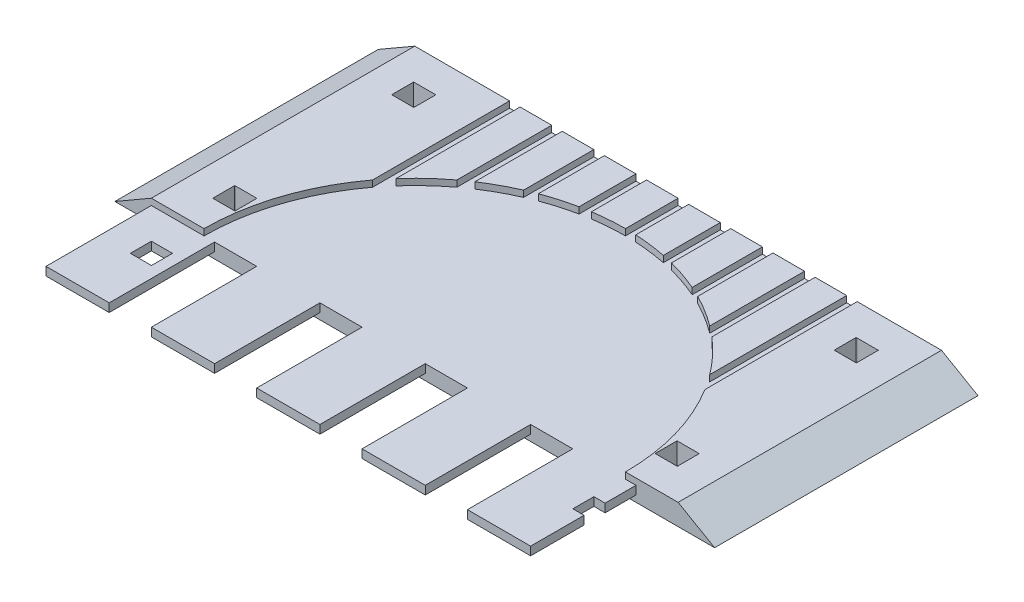
SolidWorks part; units mm, degrees
ref_plane "前视基准面" through (0, 0, 0) normal (0, 0, 1) x (1, 0, 0)
ref_plane "上视基准面" through (0, 0, 0) normal (0, 1, 0) x (1, 0, 0)
ref_plane "右视基准面" through (0, 0, 0) normal (1, 0, 0) x (0, 0, -1)
sketch "草图1" plane through (0, 0, 0) normal (0, 1, 0) x (1, 0, 0)
  line L0 (-125, 0) -> (125, 0)
  line L1 (-125, 125) -> (125, 125)
  line L2 (-125, 125) -> (-125, 0)
  line L4 (125, 125) -> (125, 0)
  line L5 (-125, 125) -> (125, -125) construction
  line L6 (-125, -125) -> (125, 125) construction
  point P0 (0, 0)
  dimension "D1" = 250
  dimension "D2" = 250
extrude "凸台-拉伸1" add sketch "草图1" along normal blind 10
sketch "草图2" plane through (0, 0, 0) normal (0, 0, 1) x (1, 0, 0)
  line L0 (-125, 7) -> (125, 7)
  line L1 (-75, 7) -> (-75, 3)
  line L2 (-125, 7) -> (-105, 7)
  line L3 (-125, 7) -> (-125, 3)
  line L4 (-125, 0) -> (125, 0)
  line L5 (125, 0) -> (125, 10)
  line L6 (125, 10) -> (-125, 10)
  line L7 (-125, 10) -> (-125, 0)
  line L8 (-125, 0) -> (125, 0)
  line L9 (125, 0) -> (125, 10)
  line L10 (125, 10) -> (-125, 10)
  line L11 (-125, 10) -> (-125, 0)
  line L12 (-125, 3) -> (-105, 3)
  line L13 (-105, 7) -> (-105, 3)
  line L14 (-105, 7) -> (-75, 7)
  line L15 (-105, 7) -> (-105, 3)
  line L16 (-105, 3) -> (-75, 3)
  line L17 (-75, 7) -> (-75, 3)
  line L18 (-75, 7) -> (-55, 7)
  line L19 (-55, 7) -> (-55, 3)
  line L20 (-75, 3) -> (-55, 3)
  line L21 (-55, 7) -> (-55, 3)
  line L22 (-55, 7) -> (-25, 7)
  line L23 (-25, 7) -> (-25, 3)
  line L24 (-55, 3) -> (-25, 3)
  line L25 (-25, 7) -> (-25, 3)
  line L26 (-25, 7) -> (-5, 7)
  line L27 (-5, 7) -> (-5, 3)
  line L28 (-25, 3) -> (-5, 3)
  line L29 (-5, 7) -> (-5, 3)
  line L30 (-5, 7) -> (25, 7)
  line L31 (25, 7) -> (25, 3)
  line L32 (-5, 3) -> (25, 3)
  line L33 (25, 7) -> (25, 3)
  line L34 (25, 7) -> (45, 7)
  line L35 (45, 7) -> (45, 3)
  line L36 (25, 3) -> (45, 3)
  line L37 (45, 7) -> (45, 3)
  line L38 (45, 7) -> (75, 7)
  line L39 (75, 7) -> (75, 3)
  line L40 (45, 3) -> (75, 3)
  line L41 (75, 7) -> (75, 3)
  line L42 (75, 7) -> (95, 7)
  line L43 (95, 7) -> (95, 3)
  line L44 (75, 3) -> (95, 3)
  line L45 (95, 7) -> (95, 3)
  line L46 (95, 7) -> (125, 7)
  line L47 (125, 7) -> (125, 3)
  line L48 (95, 3) -> (125, 3)
  dimension "D2" = 3
  dimension "D3" = 20
  dimension "D4" = 30
  dimension "D5" = 4
  dimension "D6" = 3
  dimension "D1" = 0
  dimension "D7" = 5
sketch "草图3" plane through (0, 10, 0) normal (0, 1, 0) x (1, 0, 0)
  line L0 (0, 125) -> (0, -49.5159)
  line L1 (-125, 125) -> (125, 125)
  line L2 (-125, 125) -> (-125, 0)
  line L3 (-125, 0) -> (125, 0)
  line L4 (125, 125) -> (125, 0)
  line L5 (-125, 125) -> (-105, 125)
  line L6 (-125, 125) -> (-125, 105)
  line L7 (-125, 105) -> (-105, 105)
  line L8 (-105, 125) -> (-105, 105)
  line L9 (-125, 0) -> (-105, 0)
  line L10 (-125, 0) -> (-125, 20)
  line L11 (-125, 20) -> (-105, 20)
  line L12 (-105, 0) -> (-105, 20)
  line L21 (-110, 110) -> (-100, 110)
  line L22 (-110, 110) -> (-110, 100)
  line L23 (-110, 100) -> (-100, 100)
  line L24 (-100, 110) -> (-100, 100)
  line L25 (-110, 110) -> (-100, 100) construction
  line L26 (-110, 100) -> (-100, 110) construction
  line L27 (-110, 25) -> (-100, 25)
  line L28 (-110, 25) -> (-110, 15)
  line L29 (-110, 15) -> (-100, 15)
  line L30 (-100, 25) -> (-100, 15)
  line L31 (-110, 25) -> (-100, 15) construction
  line L32 (-110, 15) -> (-100, 25) construction
  line L37 (112.5, 12.5) -> (97.5, 27.5) construction
  line L38 (112.5, 27.5) -> (97.5, 12.5) construction
  line L43 (115, 95) -> (95, 115) construction
  line L44 (115, 115) -> (95, 95) construction
  line L45 (-115, 115) -> (-95, 115)
  line L46 (-115, 115) -> (-115, 95)
  line L47 (-115, 95) -> (-95, 95)
  line L48 (-95, 115) -> (-95, 95)
  line L49 (-115, 115) -> (-95, 95) construction
  line L50 (-115, 95) -> (-95, 115) construction
  line L51 (-112.5, 27.5) -> (-97.5, 27.5)
  line L52 (-112.5, 27.5) -> (-112.5, 12.5)
  line L53 (-112.5, 12.5) -> (-97.5, 12.5)
  line L54 (-97.5, 27.5) -> (-97.5, 12.5)
  line L55 (-112.5, 27.5) -> (-97.5, 12.5) construction
  line L56 (-112.5, 12.5) -> (-97.5, 27.5) construction
  line L57 (110, 15) -> (100, 25) construction
  line L58 (110, 25) -> (100, 15) construction
  line L59 (110, 100) -> (100, 110) construction
  line L60 (110, 110) -> (100, 100) construction
  line L61 (97.5, 27.5) -> (97.5, 12.5)
  line L62 (112.5, 12.5) -> (97.5, 12.5)
  line L63 (112.5, 27.5) -> (112.5, 12.5)
  line L64 (112.5, 27.5) -> (97.5, 27.5)
  line L65 (95, 115) -> (95, 95)
  line L66 (115, 95) -> (95, 95)
  line L67 (115, 115) -> (115, 95)
  line L68 (115, 115) -> (95, 115)
  line L69 (100, 25) -> (100, 15)
  line L70 (110, 15) -> (100, 15)
  line L71 (110, 25) -> (110, 15)
  line L72 (110, 25) -> (100, 25)
  line L73 (100, 110) -> (100, 100)
  line L74 (110, 100) -> (100, 100)
  line L75 (110, 110) -> (110, 100)
  line L76 (110, 110) -> (100, 110)
  line L77 (105, 0) -> (105, 20)
  line L78 (125, 20) -> (105, 20)
  line L79 (125, 0) -> (125, 20)
  line L80 (125, 0) -> (105, 0)
  line L81 (105, 125) -> (105, 105)
  line L82 (125, 105) -> (105, 105)
  line L83 (125, 125) -> (125, 105)
  line L84 (125, 125) -> (105, 125)
  line L85 (125, 125) -> (125, 0)
  dimension "D1" = 20
  dimension "D2" = 20
  dimension "D3" = 20
  dimension "D4" = 20
  dimension "D9" = 10
  dimension "D10" = 10
  dimension "D11" = 10
  dimension "D12" = 10
  dimension "D17" = 20
  dimension "D18" = 20
  dimension "D19" = 15
  dimension "D20" = 15
sketch "草图4" plane through (0, 10, 0) normal (0, 1, 0) x (1, 0, 0)
  circle A0 centre (0, 0) radius 100
sketch "草图5" plane through (0, 10, 0) normal (0, 1, 0) x (1, 0, 0)
  line L1 (-110, 110) -> (-100, 110)
  line L2 (-110, 110) -> (-110, 100)
  line L3 (-110, 100) -> (-100, 100)
  line L4 (-100, 110) -> (-100, 100)
  line L5 (-110, 25) -> (-100, 25)
  line L6 (-110, 25) -> (-110, 15)
  line L7 (-110, 15) -> (-100, 15)
  line L8 (-100, 25) -> (-100, 15)
  line L9 (100, 110) -> (110, 110)
  line L10 (100, 110) -> (100, 100)
  line L11 (100, 100) -> (110, 100)
  line L12 (110, 110) -> (110, 100)
  line L13 (100, 25) -> (110, 25)
  line L14 (100, 25) -> (100, 15)
  line L15 (100, 15) -> (110, 15)
  line L16 (110, 25) -> (110, 15)
extrude "切除-拉伸1" cut sketch "草图5" against normal up to surface (10 mm away) up to face at (0, 0, -62.5)
sketch "草图6" plane through (0, 10, 0) normal (0, 1, 0) x (1, 0, 0)
  line L0 (-100, 0) -> (100, 0)
  arc A0 (100, 0) -> (-100, 0) centre (0, 0) ccw
extrude "切除-拉伸2" cut sketch "草图6" against normal blind 3
sketch "草图7" plane through (0, 0, 0) normal (0, 0, 1) x (1, 0, 0)
  line L0 (0, 7) -> (0, -25.8952)
  line L1 (-105, 7) -> (-75, 7)
  line L2 (-105, 7) -> (-105, 3)
  line L3 (-105, 3) -> (-75, 3)
  line L4 (-75, 7) -> (-75, 3)
  line L5 (-55, 7) -> (-25, 7)
  line L6 (-55, 7) -> (-55, 3)
  line L7 (-55, 3) -> (-25, 3)
  line L8 (-25, 7) -> (-25, 3)
  line L9 (-5, 7) -> (25, 7)
  line L10 (-5, 7) -> (-5, 3)
  line L11 (-5, 3) -> (25, 3)
  line L12 (25, 7) -> (25, 3)
  line L13 (45, 7) -> (75, 7)
  line L14 (45, 7) -> (45, 3)
  line L15 (45, 3) -> (75, 3)
  line L16 (75, 7) -> (75, 3)
  line L17 (95, 7) -> (125, 7)
  line L18 (95, 7) -> (95, 3)
  line L19 (95, 3) -> (125, 3)
  line L20 (125, 7) -> (125, 3)
sketch "草图8" plane through (0, 0, 0) normal (0, 0, 1) x (1, 0, 0)
  line L16 (-125, 7) -> (-95, 7)
  line L17 (-125, 3) -> (-125, 7)
  line L18 (-95, 3) -> (-125, 3)
  line L19 (-95, 7) -> (-95, 3)
  line L20 (-75, 7) -> (-45, 7)
  line L21 (-75, 3) -> (-75, 7)
  line L22 (-45, 3) -> (-75, 3)
  line L23 (-45, 7) -> (-45, 3)
  line L24 (-25, 7) -> (-25, 3)
  line L27 (5, 7) -> (5, 3)
  line L40 (55, 3) -> (25, 3)
  line L41 (25, 7) -> (25, 3)
  line L42 (55, 7) -> (25, 7)
  line L43 (55, 7) -> (55, 3)
  line L44 (105, 3) -> (75, 3)
  line L45 (75, 7) -> (75, 3)
  line L46 (105, 7) -> (75, 7)
  line L47 (105, 7) -> (105, 3)
  line L48 (-25, 7) -> (5, 7)
  line L49 (-25, 3) -> (5, 3)
extrude "凸台-拉伸2" add sketch "草图8" along normal blind 50
sketch "草图9" plane through (0, 7, 0) normal (0, 1, 0) x (1, 0, 0)
  line L1 (-110.323, -14.6462) -> (-100.323, -14.6462)
  line L2 (-110.323, -14.6462) -> (-110.323, -24.6462)
  line L3 (-110.323, -24.6462) -> (-100.323, -24.6462)
  line L4 (-100.323, -14.6462) -> (-100.323, -24.6462)
  line L5 (99.677, -14.6462) -> (104.677, -14.6462)
  line L6 (99.677, -14.6462) -> (99.677, -24.6462)
  line L7 (99.677, -24.6462) -> (104.677, -24.6462)
  line L8 (104.677, -14.6462) -> (104.677, -24.6462)
  line L18 (99.677, 0.3538) -> (124.677, 0.3538)
  line L19 (124.677, 0.3538) -> (124.677, 125.3538)
  line L20 (124.677, 125.3538) -> (-125.323, 125.3538)
  line L21 (-125.323, 125.3538) -> (-125.323, 0.3538)
  line L22 (-125.323, 0.3538) -> (-100.323, 0.3538)
  line L50 (-100.323, 0.3538) -> (-125.323, 0.3538)
  line L51 (-125.323, 0.3538) -> (-125.323, -49.6462)
  line L52 (-125.323, -49.6462) -> (-95.323, -49.6462)
  line L53 (-95.323, -49.6462) -> (-95.323, 0.3538)
  line L54 (-95.323, 0.3538) -> (-75.323, 0.3538)
  line L55 (-75.323, 0.3538) -> (-75.323, -49.6462)
  line L56 (-75.323, -49.6462) -> (-45.323, -49.6462)
  line L57 (-45.323, -49.6462) -> (-45.323, 0.3538)
  line L58 (-45.323, 0.3538) -> (-25.323, 0.3538)
  line L59 (-25.323, 0.3538) -> (-25.323, -49.6462)
  line L60 (-25.323, -49.6462) -> (4.677, -49.6462)
  line L61 (4.677, -49.6462) -> (4.677, 0.3538)
  line L62 (4.677, 0.3538) -> (24.677, 0.3538)
  line L63 (24.677, 0.3538) -> (24.677, -49.6462)
  line L64 (24.677, -49.6462) -> (54.677, -49.6462)
  line L65 (54.677, -49.6462) -> (54.677, 0.3538)
  line L66 (54.677, 0.3538) -> (74.677, 0.3538)
  line L67 (74.677, 0.3538) -> (74.677, -49.6462)
  line L68 (74.677, -49.6462) -> (104.677, -49.6462)
  line L69 (104.677, -49.6462) -> (104.677, 0.3538)
  line L70 (104.677, 0.3538) -> (99.677, 0.3538)
  arc A2 (99.677, 0.3538) -> (-100.323, 0.3538) centre (-0.323, 0.3538) ccw
  arc A4 (99.677, 0.3538) -> (-100.323, 0.3538) centre (-0.323, 0.3538) ccw
sketch "草图11" plane through (0, 10, 0) normal (0, 1, 0) x (1, 0, 0)
  line L0 (104.677, -14.6462) -> (112.2339, -14.6462)
  line L1 (-110.323, -14.6462) -> (-100.323, -14.6462)
  line L2 (-110.323, -14.6462) -> (-110.323, -24.6462)
  line L3 (-110.323, -24.6462) -> (-100.323, -24.6462)
  line L4 (-100.323, -14.6462) -> (-100.323, -24.6462)
  line L5 (99.677, -14.6462) -> (104.677, -14.6462)
  line L6 (99.677, -14.6462) -> (99.677, -24.6462)
  line L7 (99.677, -24.6462) -> (104.677, -24.6462)
  line L9 (112.2339, -14.6462) -> (112.2339, -24.6462)
  line L10 (112.2339, -24.6462) -> (104.677, -24.6462)
extrude "切除-拉伸4" cut sketch "草图11" against normal up to surface (10 mm away) up to face at (-105, 0, -20)
sketch "草图12" plane through (0, 10, 0) normal (0, 1, 0) x (1, 0, 0)
  line L2 (-80, 131.0287) -> (-75, 131.0287)
  line L3 (85, 131.0287) -> (85, 52.6783)
  line L4 (80, 131.0287) -> (80, 60)
  line L5 (65, 131.0287) -> (65, 75.9934)
  line L6 (60, 131.0287) -> (60, 80)
  line L7 (45, 131.0287) -> (45, 89.3029)
  line L8 (40, 131.0287) -> (40, 91.6515)
  line L9 (25, 131.0287) -> (25, 96.8246)
  line L10 (20, 131.0287) -> (20, 97.9796)
  line L11 (5, 131.0287) -> (5, 99.8749)
  line L12 (0, 131.0287) -> (0, 100)
  line L13 (-15, 131.0287) -> (-15, 98.8686)
  line L14 (-20, 131.0287) -> (-20, 97.9796)
  line L15 (-35, 131.0287) -> (-35, 93.675)
  line L16 (-40, 131.0287) -> (-40, 91.6515)
  line L17 (-55, 131.0287) -> (-55, 83.5165)
  line L18 (-60, 131.0287) -> (-60, 80)
  line L19 (-75, 131.0287) -> (-75, 66.1438)
  line L20 (-80, 131.0287) -> (-80, 60)
  line L21 (-60, 131.0287) -> (-55, 131.0287)
  line L23 (-95, 131.0287) -> (-95, 52.6783) [skipped]
  line L24 (-100, 131.0287) -> (-100, 60) [skipped]
  line L25 (-40, 131.0287) -> (-35, 131.0287)
  line L26 (-20, 131.0287) -> (-15, 131.0287)
  line L27 (0, 131.0287) -> (5, 131.0287)
  line L28 (20, 131.0287) -> (25, 131.0287)
  line L29 (40, 131.0287) -> (45, 131.0287)
  line L30 (60, 131.0287) -> (65, 131.0287)
  line L31 (80, 131.0287) -> (85, 131.0287)
  circle A0 centre (0, 0) radius 100 construction
  arc A1 (85, 52.6783) -> (80, 60) centre (0, 0) ccw
  arc A2 (-75, 66.1438) -> (-80, 60) centre (0, 0) ccw
  arc A3 (-55, 83.5165) -> (-60, 80) centre (0, 0) ccw
  arc A4 (-35, 93.675) -> (-40, 91.6515) centre (0, 0) ccw
  arc A5 (-15, 98.8686) -> (-20, 97.9796) centre (0, 0) ccw
  arc A6 (5, 99.8749) -> (0, 100) centre (0, 0) ccw
  arc A7 (25, 96.8246) -> (20, 97.9796) centre (0, 0) ccw
  arc A8 (45, 89.3029) -> (40, 91.6515) centre (0, 0) ccw
  arc A9 (65, 75.9934) -> (60, 80) centre (0, 0) ccw
  dimension "D2" = 5
  dimension "D3" = 10
extrude "切除-拉伸5" cut sketch "草图12" against normal up to surface (3 mm away) up to face at (-105.323, 7, 19.6462)
sketch "草图13" plane through (0, 0, -125) normal (0, 0, -1) x (-1, 0, 0)
  line L0 (125, 10) -> (125, 0)
  line L1 (125, 0) -> (142.3205, 0)
  line L2 (142.3205, 0) -> (125, 10)
  line L3 (-125, 10) -> (-125, 0)
  line L4 (-125, 0) -> (-142.3205, 0)
  line L5 (-142.3205, 0) -> (-125, 10)
  dimension "D1" = 30
  dimension "D2" = 30
extrude "凸台-拉伸3" add sketch "草图13" against normal up to surface (125 mm away) up to face at (10.4167, 5, 0)
sketch "草图14" plane through (0, 0, 0) normal (0, -1, 0) x (1, 0, 0)
  line L0 (-92.3205, -125) -> (-92.3205, -55.4041)
  line L1 (-92.3205, -55.4041) -> (-62.3205, -55.4041)
  line L2 (-62.3205, -55.4041) -> (-62.3205, -125)
  line L3 (-92.3205, -125) -> (-62.3205, -125)
  line L4 (-17.3205, -125) -> (12.6795, -125)
  line L5 (12.6795, -55.4041) -> (12.6795, -125)
  line L6 (-17.3205, -55.4041) -> (12.6795, -55.4041)
  line L7 (-17.3205, -125) -> (-17.3205, -55.4041)
  line L12 (57.6795, -125) -> (87.6795, -125)
  line L13 (87.6795, -55.4041) -> (87.6795, -125)
  line L14 (57.6795, -55.4041) -> (87.6795, -55.4041)
  line L15 (57.6795, -125) -> (57.6795, -55.4041)
  dimension "D3" = 30
  dimension "D1" = 3
extrude "切除-拉伸6" cut sketch "草图14" against normal blind 5
sketch "草图15" plane through (0, 0, 0) normal (0, -1, 0) x (1, 0, 0)
  line L4 (57.6795, -125) -> (87.6795, -125)
  line L5 (87.6795, -125) -> (87.6795, -55.4041)
  line L6 (87.6795, -55.4041) -> (57.6795, -55.4041)
  line L7 (57.6795, -55.4041) -> (57.6795, -125)
  line L8 (57.6795, -125) -> (87.6795, -125)
  line L9 (87.6795, -125) -> (87.6795, -55.4041)
  line L10 (87.6795, -55.4041) -> (57.6795, -55.4041)
  line L11 (57.6795, -55.4041) -> (57.6795, -125)
  line L12 (-17.3205, -125) -> (12.6795, -125)
  line L13 (12.6795, -125) -> (12.6795, -55.4041)
  line L14 (12.6795, -55.4041) -> (-17.3205, -55.4041)
  line L15 (-17.3205, -55.4041) -> (-17.3205, -125)
  line L16 (-17.3205, -125) -> (12.6795, -125)
  line L17 (12.6795, -125) -> (12.6795, -55.4041)
  line L18 (12.6795, -55.4041) -> (-17.3205, -55.4041)
  line L19 (-17.3205, -55.4041) -> (-17.3205, -125)
  line L20 (-92.3205, -55.4041) -> (-92.3205, -125)
  line L21 (-62.3205, -55.4041) -> (-92.3205, -55.4041)
  line L22 (-62.3205, -125) -> (-62.3205, -55.4041)
  line L23 (-92.3205, -125) -> (-62.3205, -125)
  line L24 (-92.3205, -55.4041) -> (-92.3205, -125)
  line L25 (-62.3205, -55.4041) -> (-92.3205, -55.4041)
  line L26 (-62.3205, -125) -> (-62.3205, -55.4041)
  line L27 (-92.3205, -125) -> (-62.3205, -125)
  line L40 (-142.3205, -125) -> (-92.3205, -125)
  line L41 (-92.3205, -125) -> (-92.3205, -55.4041)
  line L42 (-92.3205, -55.4041) -> (-62.3205, -55.4041)
  line L43 (-62.3205, -55.4041) -> (-62.3205, -125)
  line L44 (-62.3205, -125) -> (-17.3205, -125)
  line L45 (-17.3205, -125) -> (-17.3205, -55.4041)
  line L46 (-17.3205, -55.4041) -> (12.6795, -55.4041)
  line L47 (12.6795, -55.4041) -> (12.6795, -125)
  line L48 (12.6795, -125) -> (57.6795, -125)
  line L49 (57.6795, -125) -> (57.6795, -55.4041)
  line L50 (57.6795, -55.4041) -> (87.6795, -55.4041)
  line L51 (87.6795, -55.4041) -> (87.6795, -125)
  line L52 (87.6795, -125) -> (142.3205, -125)
  line L53 (142.3205, -125) -> (142.3205, 0)
  line L54 (142.3205, 0) -> (-142.3205, 0)
  line L55 (-142.3205, 0) -> (-142.3205, -125)
  line L56 (-142.3205, -125) -> (-92.3205, -125)
  line L57 (-92.3205, -125) -> (-92.3205, -55.4041)
  line L58 (-92.3205, -55.4041) -> (-62.3205, -55.4041)
  line L59 (-62.3205, -55.4041) -> (-62.3205, -125)
  line L60 (-62.3205, -125) -> (-17.3205, -125)
  line L61 (-17.3205, -125) -> (-17.3205, -55.4041)
  line L62 (-17.3205, -55.4041) -> (12.6795, -55.4041)
  line L63 (12.6795, -55.4041) -> (12.6795, -125)
  line L64 (12.6795, -125) -> (57.6795, -125)
  line L65 (57.6795, -125) -> (57.6795, -55.4041)
  line L66 (57.6795, -55.4041) -> (87.6795, -55.4041)
  line L67 (87.6795, -55.4041) -> (87.6795, -125)
  line L68 (87.6795, -125) -> (142.3205, -125)
  line L69 (142.3205, -125) -> (142.3205, 0)
  line L70 (142.3205, 0) -> (-142.3205, 0)
  line L71 (-142.3205, 0) -> (-142.3205, -125)
  dimension "D1" = 0
  dimension "D2" = 0
  dimension "D3" = 0
  dimension "D4" = 0
sketch "草图16" plane through (0, 10, 0) normal (0, 1, 0) x (1, 0, 0)
  line L1 (-100, 110) -> (-110.5174, 110)
  line L2 (-100, 110) -> (-100, 99.5766)
  line L3 (-100, 99.5766) -> (-110.5174, 99.5766)
  line L4 (-110.5174, 110) -> (-110.5174, 99.5766)
  line L5 (109.9797, 25.0347) -> (99.4623, 25.0347)
  line L6 (109.9797, 25.0347) -> (109.9797, 14.6113)
  line L7 (109.9797, 14.6113) -> (99.4623, 14.6113)
  line L8 (99.4623, 25.0347) -> (99.4623, 14.6113)
  line L9 (-99.8962, 24.9877) -> (-110.4136, 24.9877)
  line L10 (-99.8962, 24.9877) -> (-99.8962, 14.5643)
  line L11 (-99.8962, 14.5643) -> (-110.4136, 14.5643)
  line L12 (-110.4136, 24.9877) -> (-110.4136, 14.5643)
  line L13 (110.0037, 109.9988) -> (99.4863, 109.9988)
  line L14 (110.0037, 109.9988) -> (110.0037, 99.5754)
  line L15 (110.0037, 99.5754) -> (99.4863, 99.5754)
  line L16 (99.4863, 109.9988) -> (99.4863, 99.5754)
extrude "切除-拉伸7" cut sketch "草图16" against normal through all
